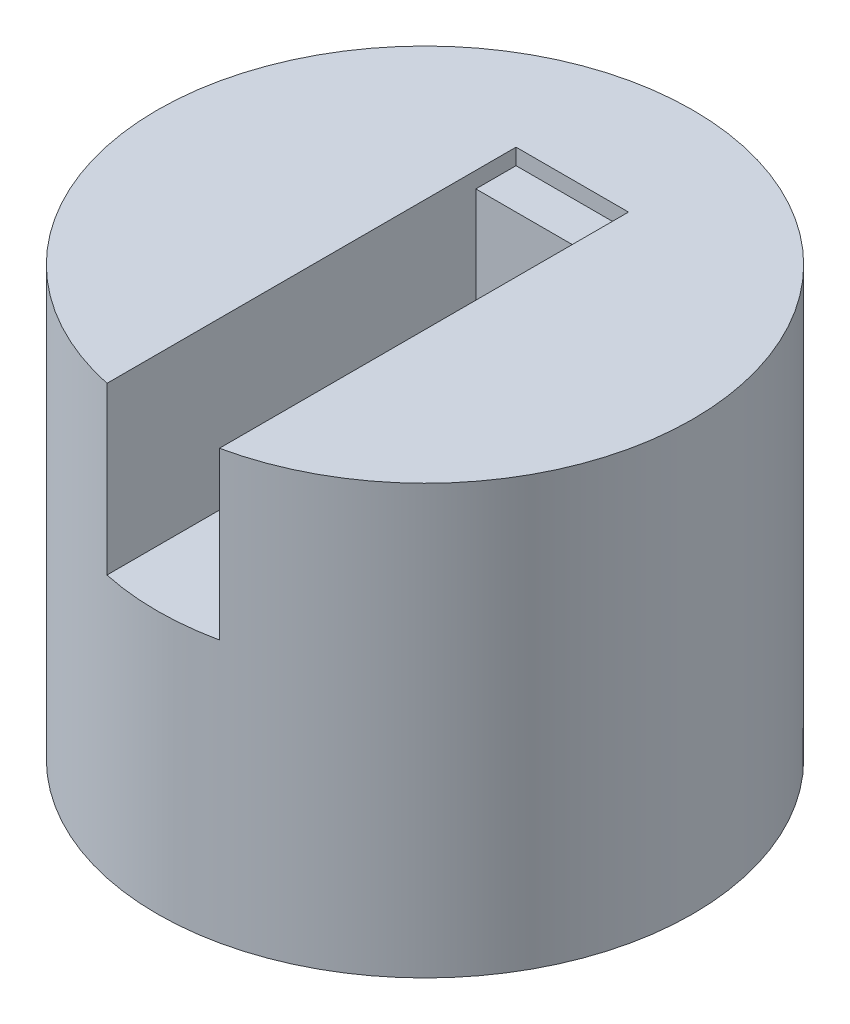
SolidWorks part; units mm, degrees
ref_plane "Front Plane" through (0, 0, 0) normal (0, 0, 1) x (1, 0, 0)
ref_plane "Top Plane" through (0, 0, 0) normal (0, 1, 0) x (1, 0, 0)
ref_plane "Right Plane" through (0, 0, 0) normal (1, 0, 0) x (0, 0, -1)
sketch "Sketch2" plane through (0, 0, 0) normal (0, 1, 0) x (1, 0, 0)
  circle A0 centre (0, 0) radius 50
  dimension "D1" = 100
extrude "Boss-Extrude1" add sketch "Sketch2" along normal blind 80
sketch "Sketch3" plane through (0, 80, 0) normal (0, 1, 0) x (1, 0, 0)
  line L1 (-10.5, 27.5) -> (10.5, 27.5)
  line L2 (-10.5, 27.5) -> (-10.5, -27.5)
  line L3 (-10.5, -27.5) -> (10.5, -27.5)
  line L4 (10.5, 27.5) -> (10.5, -27.5)
  line L5 (-10.5, 27.5) -> (10.5, -27.5) construction
  line L6 (-10.5, -27.5) -> (10.5, 27.5) construction
  point P0 (0, 0)
  dimension "D1" = 55
  dimension "D2" = 21
extrude "Cut-Extrude2" cut sketch "Sketch3" against normal blind 3
sketch "Sketch4" plane through (0, 77, 0) normal (0, 1, 0) x (1, 0, 0)
  line L0 (10.5, -27.5) -> (10.5, 27.5) construction
  line L1 (-10.5, 20) -> (10.5, 20)
  line L2 (-10.5, 20) -> (-10.5, -20)
  line L3 (-10.5, -20) -> (10.5, -20)
  line L4 (10.5, 20) -> (10.5, -20)
  line L5 (-10.5, 20) -> (10.5, -20) construction
  line L6 (-10.5, -20) -> (10.5, 20) construction
  point P0 (0, 0)
  dimension "D1" = 40
extrude "Cut-Extrude3" cut sketch "Sketch4" against normal blind 28
sketch "Sketch5" plane through (0, 80, 0) normal (0, 1, 0) x (1, 0, 0)
  line L0 (-10.5, 27.5) -> (-10.5, -27.5) construction
  line L1 (-10.5, 0) -> (10.5, 0)
  line L2 (-10.5, 0) -> (-10.5, -56.8624)
  line L3 (-10.5, -56.8624) -> (10.5, -56.8624)
  line L4 (10.5, 0) -> (10.5, -56.8624)
  line L5 (10.5, -27.5) -> (10.5, 27.5) construction
  point P6 (0, 0)
extrude "Cut-Extrude4" cut sketch "Sketch5" against normal up to surface (31 mm away) from surface at 0 up to face at (0, 49, 0) starting at face at (0, 80, 0)
